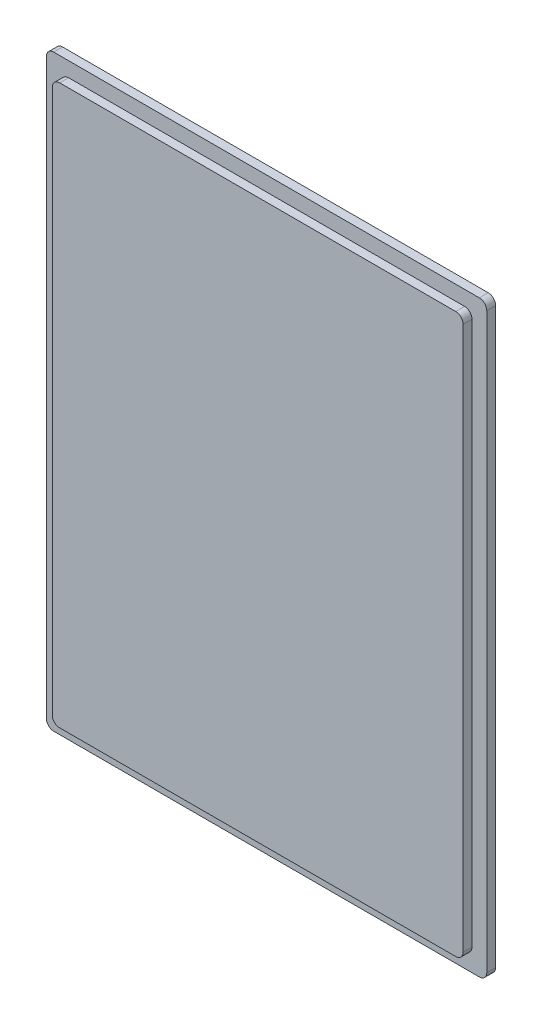
SolidWorks part; units mm, degrees
ref_plane "Front Plane" through (0, 0, 0) normal (0, 0, 1) x (1, 0, 0)
ref_plane "Top Plane" through (0, 0, 0) normal (0, 1, 0) x (1, 0, 0)
ref_plane "Right Plane" through (0, 0, 0) normal (1, 0, 0) x (0, 0, -1)
sketch "Sketch1" plane through (0, 0, 0) normal (0, 0, 1) x (1, 0, 0)
  line L0 (-49.8047, 16.5341) -> (-49.8047, -371.4659)
  line L1 (-44.8047, -376.4659) -> (243.1953, -376.4659)
  line L2 (248.1953, -371.4659) -> (248.1953, 16.5341)
  line L3 (243.1953, 21.5341) -> (-44.8047, 21.5341)
  arc A0 (-49.8047, -371.4659) -> (-44.8047, -376.4659) centre (-44.8047, -371.4659) ccw
  arc A1 (243.1953, -376.4659) -> (248.1953, -371.4659) centre (243.1953, -371.4659) ccw
  arc A2 (248.1953, 16.5341) -> (243.1953, 21.5341) centre (243.1953, 16.5341) ccw
  arc A3 (-44.8047, 21.5341) -> (-49.8047, 16.5341) centre (-44.8047, 16.5341) ccw
  dimension "D1" = 5
extrude "Boss-Extrude1" add sketch "Sketch1" along normal blind 6
sketch "Sketch2" plane through (0, 0, 6) normal (0, 0, 1) x (1, 0, 0)
  line L0 (-39.8047, 6.5341) -> (-39.8047, -361.4659)
  line L1 (-49.8047, 16.5341) -> (-49.8047, -371.4659) construction
  line L2 (243.1953, 21.5341) -> (-44.8047, 21.5341) construction
  line L3 (-44.8047, -376.4659) -> (243.1953, -376.4659) construction
  line L4 (-34.8047, 11.5341) -> (233.1953, 11.5341)
  line L5 (248.1953, -371.4659) -> (248.1953, 16.5341) construction
  line L6 (238.1953, 6.5341) -> (238.1953, -361.4659)
  line L7 (233.1953, -366.4659) -> (-34.8047, -366.4659)
  arc A0 (-39.8047, -361.4659) -> (-34.8047, -366.4659) centre (-34.8047, -361.4659) ccw
  arc A1 (233.1953, -366.4659) -> (238.1953, -361.4659) centre (233.1953, -361.4659) ccw
  arc A2 (238.1953, 6.5341) -> (233.1953, 11.5341) centre (233.1953, 6.5341) ccw
  arc A3 (-34.8047, 11.5341) -> (-39.8047, 6.5341) centre (-34.8047, 6.5341) ccw
  point P14 (-39.8047, -366.4659)
  point P19 (238.1953, 11.5341)
  point P22 (-39.8047, 11.5341)
  dimension "D5" = 5
  dimension "D1" = 10
  dimension "D2" = 10
  dimension "D3" = 10
  dimension "D4" = 10
extrude "Boss-Extrude2" add sketch "Sketch2" along normal blind 6 contours A1 L7 A0 L0 A3 L4 A2 L6
